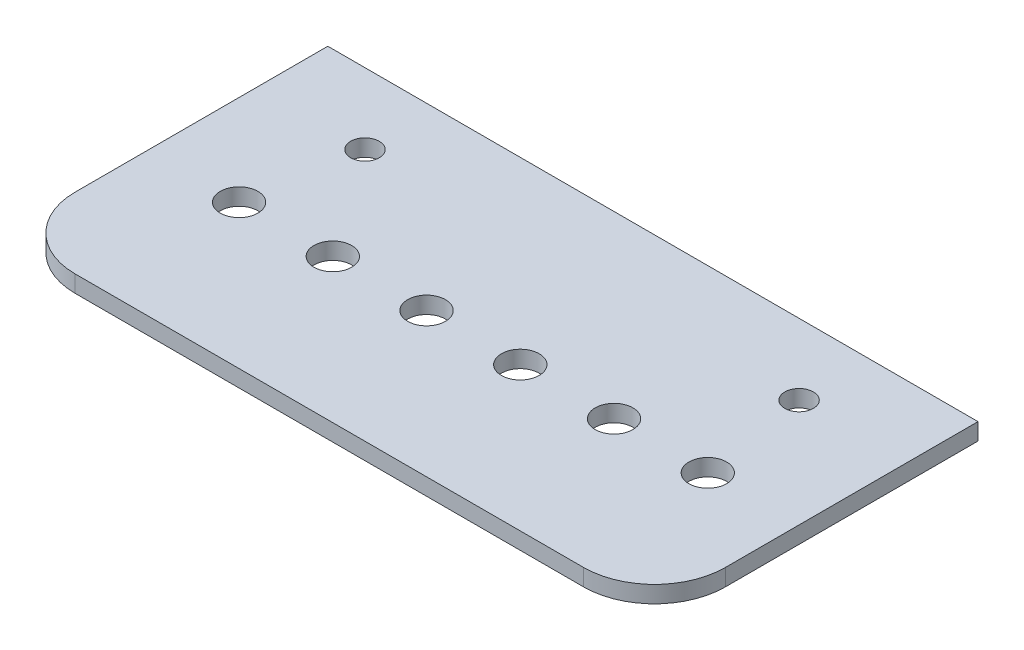
SolidWorks part; units mm, degrees
ref_plane "Front Plane" through (0, 0, 0) normal (0, 0, 1) x (1, 0, 0)
ref_plane "Top Plane" through (0, 0, 0) normal (0, 1, 0) x (1, 0, 0)
ref_plane "Right Plane" through (0, 0, 0) normal (1, 0, 0) x (0, 0, -1)
sketch "Sketch1" plane through (0, 0, 0) normal (0, 1, 0) x (1, 0, 0)
  line L0 (-44.475, 0) -> (44.475, 0)
  line L1 (56.875, 12.4) -> (56.875, 56.6)
  line L2 (56.875, 56.6) -> (-56.875, 56.6)
  line L3 (-56.875, 56.6) -> (-56.875, 12.4)
  arc A0 (44.475, 0) -> (56.875, 12.4) centre (44.475, 12.4) ccw
  arc A1 (-56.875, 12.4) -> (-44.475, 0) centre (-44.475, 12.4) ccw
  point P4 (0, 0)
  dimension "D1" = 12.4
  dimension "D2" = 113.75
  dimension "D3" = 56.6
extrude "Boss-Extrude1" add sketch "Sketch1" along normal blind 2.95
sketch "Sketch5" plane through (0, 2.95, 0) normal (0, 1, 0) x (1, 0, 0)
  line L1 (-44.475, 0) -> (44.475, 0) construction
  line L2 (-41, 25.2) -> (-24.6, 25.2) construction
  line L3 (-8.2, 25.2) -> (8.2, 25.2) construction
  circle A0 centre (-41, 25.2) radius 3.3
  circle A1 centre (-24.6, 25.2) radius 3.3
  circle A2 centre (-8.2, 25.2) radius 3.3
  circle A3 centre (8.2, 25.2) radius 3.3
  circle A4 centre (24.6, 25.2) radius 3.3
  circle A5 centre (41, 25.2) radius 3.3
  point P0 (0, 25.2)
  point P4 (0, 0)
  dimension "D1" = 21.9
  dimension "D2" = 6.6
  dimension "D4" = 9.8
  dimension "D3" = 6
extrude "Hole1" cut sketch "Sketch5" against normal through all
sketch "Sketch7" plane through (0, 2.95, 0) normal (0, 1, 0) x (1, 0, 0)
  line L0 (-56.875, 56.6) -> (-56.875, 12.4) construction
  line L1 (56.875, 56.6) -> (-56.875, 56.6) construction
  circle A0 centre (-37.975, 44.2) radius 2.5
  dimension "D1" = 5
  dimension "D2" = 16.4
  dimension "D3" = 9.9
extrude "Cut-Extrude2" cut sketch "Sketch7" against normal through all
mirror "Mirror1" about plane through (0, 0, 0) normal (1, 0, 0) of "Cut-Extrude2"
